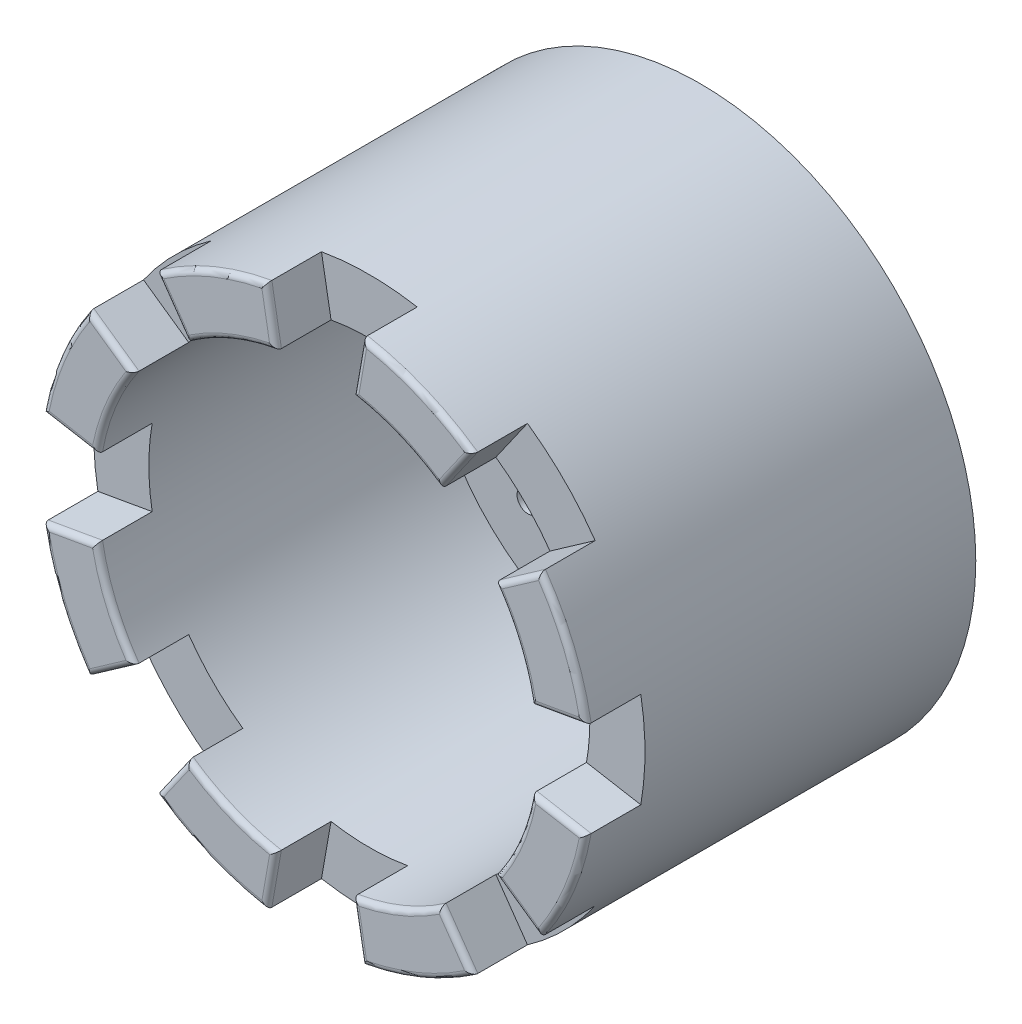
SolidWorks part; units mm, degrees
ref_plane "Alzado" through (0, 0, 0) normal (0, 0, 1) x (1, 0, 0)
ref_plane "Planta" through (0, 0, 0) normal (0, 1, 0) x (1, 0, 0)
ref_plane "Vista lateral" through (0, 0, 0) normal (1, 0, 0) x (0, 0, -1)
sketch "Croquis1" plane through (0, 0, 0) normal (0, 0, 1) x (1, 0, 0)
  circle A0 centre (0, 0) radius 50
  circle A1 centre (0, 0) radius 15.5
  point P4 (0, 0)
  dimension "D1" = 100
  dimension "D2" = 31
extrude "Saliente-Extruir1" add sketch "Croquis1" along normal blind 70
sketch "Croquis2" plane through (0, 0, 70) normal (0, 0, 1) x (1, 0, 0)
  circle A0 centre (0, 0) radius 40
  dimension "D1" = 80
extrude "Cortar-Extruir1" cut sketch "Croquis2" against normal blind 50
sketch "Croquis3" plane through (0, 0, 0) normal (0, 0, -1) x (-1, 0, 0)
  circle A0 centre (0, 0) radius 17.5
  dimension "D1" = 35
extrude "Cortar-Extruir2" cut sketch "Croquis3" against normal blind 10
sketch "Croquis4" plane through (0, 0, 20) normal (0, 0, 1) x (1, 0, 0)
  line L1 (-2.5, 32.5) -> (2.5, 32.5)
  line L2 (-2.5, 32.5) -> (-2.5, 22.5)
  line L3 (-2.5, 22.5) -> (2.5, 22.5)
  line L4 (2.5, 32.5) -> (2.5, 22.5)
  line L5 (-2.5, 32.5) -> (2.5, 22.5) construction
  line L6 (-2.5, 22.5) -> (2.5, 32.5) construction
  line L7 (32.5, -2.5) -> (22.5, -2.5)
  line L8 (32.5, -2.5) -> (32.5, 2.5)
  line L9 (32.5, 2.5) -> (22.5, 2.5)
  line L10 (22.5, -2.5) -> (22.5, 2.5)
  line L11 (32.5, -2.5) -> (22.5, 2.5) construction
  line L12 (32.5, 2.5) -> (22.5, -2.5) construction
  line L13 (2.5, -32.5) -> (-2.5, -32.5)
  line L14 (2.5, -32.5) -> (2.5, -22.5)
  line L15 (2.5, -22.5) -> (-2.5, -22.5)
  line L16 (-2.5, -32.5) -> (-2.5, -22.5)
  line L17 (2.5, -32.5) -> (-2.5, -22.5) construction
  line L18 (2.5, -22.5) -> (-2.5, -32.5) construction
  line L19 (-32.5, -2.5) -> (-22.5, -2.5)
  line L20 (-32.5, -2.5) -> (-32.5, 2.5)
  line L21 (-32.5, 2.5) -> (-22.5, 2.5)
  line L22 (-22.5, -2.5) -> (-22.5, 2.5)
  line L23 (-32.5, -2.5) -> (-22.5, 2.5) construction
  line L24 (-32.5, 2.5) -> (-22.5, -2.5) construction
  circle A0 centre (0, 0) radius 40
  circle A1 centre (0, 0) radius 27.5
  point P4 (0, 27.5)
  point P9 (27.5, 0)
  point P14 (0, -27.5)
  point P19 (-27.5, 0)
  circle M10 centre (0, 0) radius 15.5
  circle M11 centre (0, 0) radius 40
  dimension "D1" = 80
  dimension "D2" = 55
  dimension "D3" = 10
  dimension "D4" = 5
  dimension "D5" = 5
  dimension "D6" = 10
  dimension "D7" = 5
  dimension "D8" = 10
  dimension "D9" = 5
  dimension "D10" = 10
extrude "Cortar-Extruir3" cut sketch "Croquis4" against normal blind 10 contours A1 L9 L8 L7 L14 L13 L16 L19 L20 L21 L2 L1 L4 M11 | L9 A1 L4 L3 L2 L21 L22 L19 L16 L15 L14 L7 L10 M10
sketch "Croquis5" plane through (0, 0, 10) normal (0, 0, 1) x (1, 0, 0)
  line L0 (0, 0) -> (28.2843, 28.2843) construction
  circle A0 centre (21.2132, 21.2132) radius 2
  circle A1 centre (21.2132, -21.2132) radius 2
  circle A2 centre (-21.2132, -21.2132) radius 2
  circle A3 centre (-21.2132, 21.2132) radius 2
  point P14 (0, 0)
  dimension "D2" = 4
  dimension "D1" = 40
  dimension "D4" = 30
  dimension "D3" = 4
extrude "Cortar-Extruir4" cut sketch "Croquis5" against normal through all
sketch "Croquis6" plane through (0, 0, 0) normal (0, 0, -1) x (-1, 0, 0)
  circle A0 centre (-21.2132, 21.2132) radius 5
  circle A1 centre (21.487, 21.487) radius 5
  circle A2 centre (21.7607, -21.2132) radius 5
  circle A3 centre (-20.9394, -21.487) radius 5
  point P12 (0.2738, 0)
  dimension "D1" = 10
  dimension "D2" = 4
extrude "Cortar-Extruir5" cut sketch "Croquis6" against normal blind 5
sketch "Croquis7" plane through (0, 0, 70) normal (0, 0, 1) x (1, 0, 0)
  line L0 (0, 0) -> (0, 50)
  line L1 (0, 0) -> (8.6824, 49.2404)
  line L2 (0, 0) -> (-8.6824, 49.2404)
  line L3 (0, 0) -> (40.9576, 28.6788)
  line L4 (0, 0) -> (28.6788, 40.9576)
  line L5 (0, 0) -> (49.2404, -8.6824)
  line L6 (0, 0) -> (49.2404, 8.6824)
  line L7 (0, 0) -> (28.6788, -40.9576)
  line L8 (0, 0) -> (40.9576, -28.6788)
  line L9 (0, 0) -> (-8.6824, -49.2404)
  line L10 (0, 0) -> (8.6824, -49.2404)
  line L11 (0, 0) -> (-40.9576, -28.6788)
  line L12 (0, 0) -> (-28.6788, -40.9576)
  line L13 (0, 0) -> (-49.2404, 8.6824)
  line L14 (0, 0) -> (-49.2404, -8.6824)
  line L15 (0, 0) -> (-28.6788, 40.9576)
  line L16 (0, 0) -> (-40.9576, 28.6788)
  circle A0 centre (0, 0) radius 50 construction
  circle A1 centre (0, 0) radius 40
  circle A2 centre (0, 0) radius 50
  point P27 (0, 0)
  circle M5 centre (0, 0) radius 40
  circle M6 centre (0, 0) radius 50
  dimension "D3" = 100
  dimension "D4" = 80
  dimension "D1" = 10
  dimension "D2" = 10
  dimension "D5" = 8
extrude "Cortar-Extruir6" cut sketch "Croquis7" against normal blind 10 contours L2 L0 M5 M6 | L1 L0 M5 M6 | L4 L3 M5 M6 | L6 L5 M5 M6 | L8 L7 M5 M6 | L16 L15 M5 M6 | L14 L13 M5 M6 | L12 L11 M5 M6 | L10 L9 M5 M6
fillet "Redondeo2" radius 1 48 edges at (7.8142, 44.3163, 70) (19.1342, 46.194, 70) (25.8109, 36.8618, 70) (15.3073, 36.9552, 70) (36.8618, 25.8109, 70) (46.194, 19.1342, 70) (44.3163, 7.8142, 70) (36.9552, 15.3073, 70) (44.3163, -7.8142, 70) (46.194, -19.1342, 70) (36.8618, -25.8109, 70) (36.9552, -15.3073, 70) (19.1342, -46.194, 70) (7.8142, -44.3163, 70) (15.3073, -36.9552, 70) (25.8109, -36.8618, 70) (-7.8142, -44.3163, 70) (-19.1342, -46.194, 70) (-25.8109, -36.8618, 70) (-15.3073, -36.9552, 70) (-19.1342, 46.194, 70) (-7.8142, 44.3163, 70) (-15.3073, 36.9552, 70) (-25.8109, 36.8618, 70) (-36.8618, -25.8109, 70) (-46.194, -19.1342, 70) (-44.3163, -7.8142, 70) (-36.9552, -15.3073, 70) (-44.3163, 7.8142, 70) (-46.194, 19.1342, 70) (-36.8618, 25.8109, 70) (-36.9552, 15.3073, 70) (0, -22.5, 20) (2.5, -27.5, 20) (0, -32.5, 20) (-2.5, -27.5, 20) (-32.5, 0, 20) (-27.5, 2.5, 20) (-22.5, 0, 20) (-27.5, -2.5, 20) (22.5, 0, 20) (27.5, 2.5, 20) (32.5, 0, 20) (27.5, -2.5, 20) (0, 22.5, 20) (-2.5, 27.5, 20) (0, 32.5, 20) (2.5, 27.5, 20)
